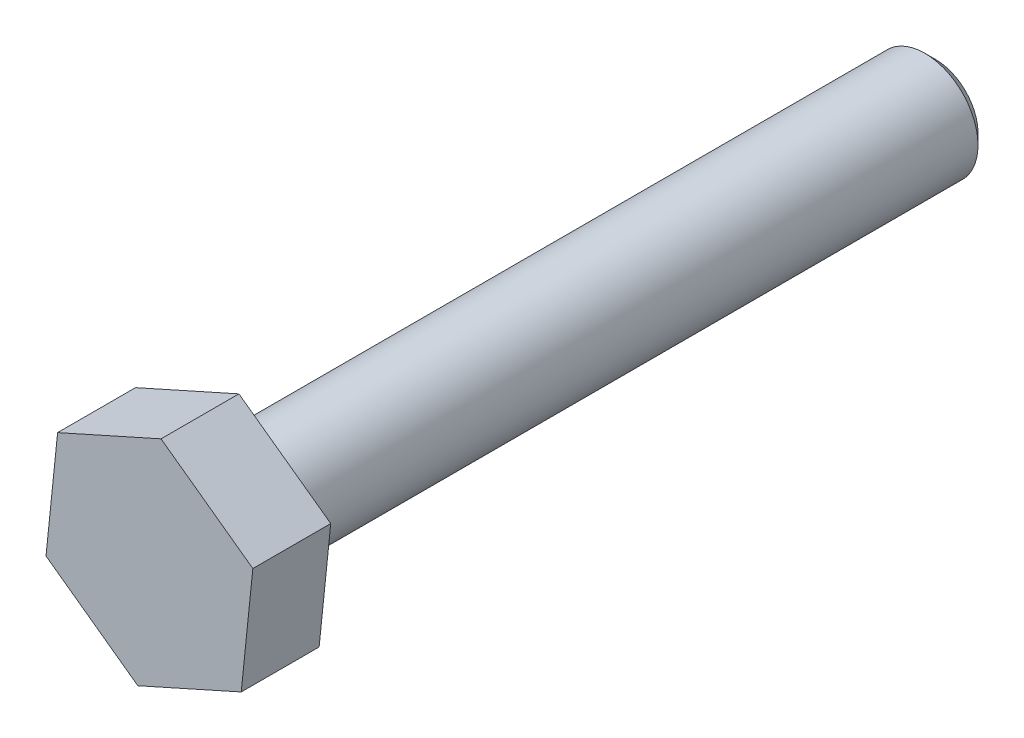
SolidWorks part; units mm, degrees
ref_plane "Front Plane" through (0, 0, 0) normal (0, 0, 1) x (1, 0, 0)
ref_plane "Top Plane" through (0, 0, 0) normal (0, 1, 0) x (1, 0, 0)
ref_plane "Right Plane" through (0, 0, 0) normal (1, 0, 0) x (0, 0, -1)
sketch "Sketch1" plane through (0, 0, 0) normal (0, 0, 1) x (1, 0, 0)
  line L1 (2.5928, -1.8755) -> (2.9206, 1.3076)
  line L2 (2.9206, 1.3076) -> (0.3279, 3.1832)
  line L3 (0.3279, 3.1832) -> (-2.5928, 1.8755)
  line L4 (-2.5928, 1.8755) -> (-2.9206, -1.3076)
  line L5 (-2.9206, -1.3076) -> (-0.3279, -3.1832)
  line L6 (-0.3279, -3.1832) -> (2.5928, -1.8755)
  circle A0 centre (0, 0) radius 2.85 construction
  circle A1 centre (0, 0) radius 3.2 construction
  dimension "D1" = 5.7
  dimension "D2" = 6.4
extrude "Boss-Extrude1" add sketch "Sketch1" along normal blind 2.2
sketch "Sketch2" plane through (0, 0, 0) normal (0, 0, -1) x (-1, 0, 0)
  circle A0 centre (0, 0) radius 1.5
  dimension "D1" = 3
extrude "Boss-Extrude2" add sketch "Sketch2" along normal blind 20
cosmetic thread "Cosmetic Thread1"
chamfer "Chamfer1" distance 0.3 angle 45 1 edges at (-1.5, 0, -20)
